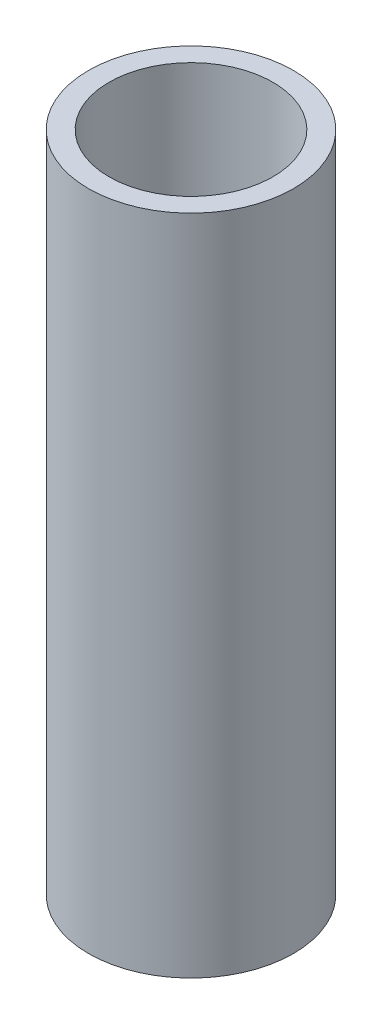
SolidWorks part; units mm, degrees
material "Brass"
ref_plane "Front Plane" through (0, 0, 0) normal (0, 0, 1) x (1, 0, 0)
ref_plane "Top Plane" through (0, 0, 0) normal (0, 1, 0) x (1, 0, 0)
ref_plane "Right Plane" through (0, 0, 0) normal (1, 0, 0) x (0, 0, -1)
sketch "Sketch1" plane through (0, 0, 0) normal (0, 1, 0) x (1, 0, 0)
  circle A0 centre (0, 0) radius 0.375
  dimension "D1" = 0.75
extrude "Boss-Extrude1" add sketch "Sketch1" along normal blind 2.425
hole_wizard "Ø0.6 (0.6) Diameter Hole1" positions "Sketch3" profile "Sketch2" hole size "Ø0.6" standard "ANSI Metric"
sketch "Sketch3" plane through (0, 2.425, 0) normal (0, 1, 0) x (-1, 0, 0)
  point P0 (0, 0)
sketch "Sketch2" plane through (0, 2.425, 0) normal (1, 0, 0) x (0, 0, 1)
  line L0 (0, 0) -> (0, 11.5103)
  line L1 (0, 11.5103) -> (0.3, 11.33)
  line L2 (0.3, 11.33) -> (0.3, 0)
  line L5 (0.3, 0) -> (0, 0)
  line L10 (0, 11.5103) -> (-0.3, 11.33) construction
  line L11 (0, -6.35) -> (0, 107.95) construction
  dimension "Hole Dia." = 0.6
  dimension "Hole Depth" = 11.33
  dimension "Drill Angle" = 118
